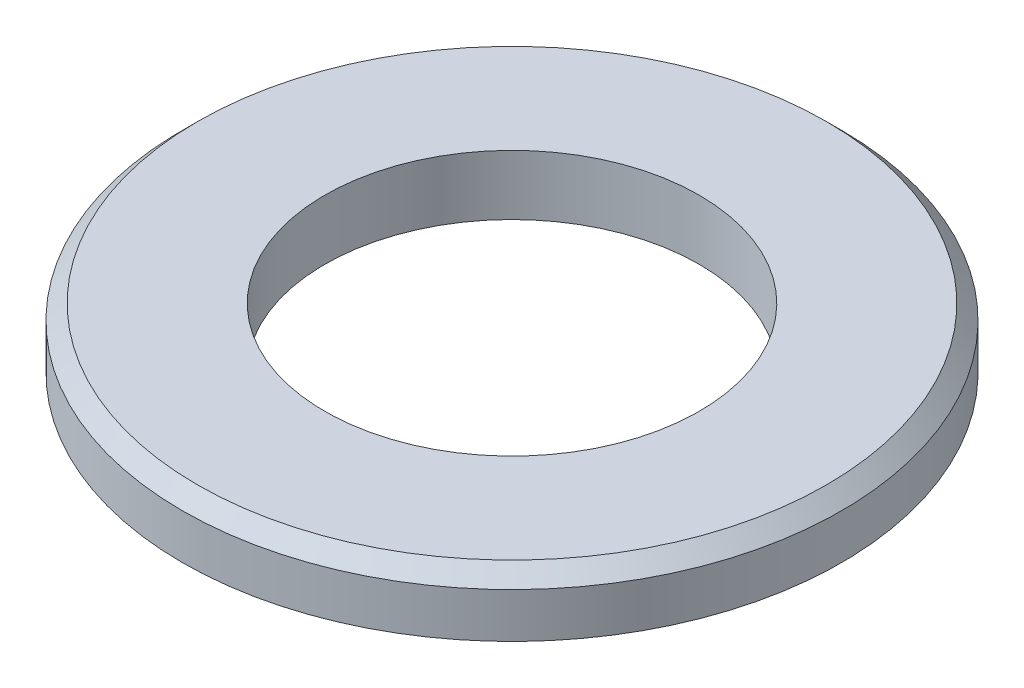
SolidWorks part; units mm, degrees
ref_plane "基准面1" through (0, 0, 0) normal (0, 0, 1) x (1, 0, 0)
ref_plane "基准面2" through (0, 0, 0) normal (0, 1, 0) x (1, 0, 0)
ref_plane "基准面3" through (0, 0, 0) normal (1, 0, 0) x (0, 0, -1)
sketch "尺寸草图" plane through (0, 0, 0) normal (0, 0, 1) x (1, 0, 0)
  line L0 (0, 0) -> (9.1, 0)
  point P3 (4, 0)
  point P4 (44, 0)
  point P5 (25, 0)
  dimension "h" = 4
  dimension "d2" = 44
  dimension "d1" = 25
sketch "草图1" plane through (0, 0, 0) normal (0, 0, 1) x (1, 0, 0)
  line L0 (0, 0) -> (0, 52.7318) construction
  line L1 (-21, 12.6445) -> (-22, 11.6445)
  line L2 (-12.5, 8.6445) -> (-22, 8.6445)
  line L3 (-12.5, 8.6445) -> (-12.5, 12.6445)
  line L4 (-12.5, 12.6445) -> (-21, 12.6445)
  line L5 (-22, 8.6445) -> (-22, 11.6445)
  point P4 (-22, 12.6445)
  dimension "h" = 4
  dimension "D1" = 12.5
  dimension "D2" = 22
revolve "基体-旋转" add sketch "草图1" angle 360 about L0
equation "\"h@草图1\" = \"h@尺寸草图\""
equation "\"D1@草图1\" = \"d1@尺寸草图\" / 2"
equation "\"D2@草图1\" = \"d2@尺寸草图\" / 2"
equation "\"D5@草图1\" = \"h@草图1\" *0.25"
